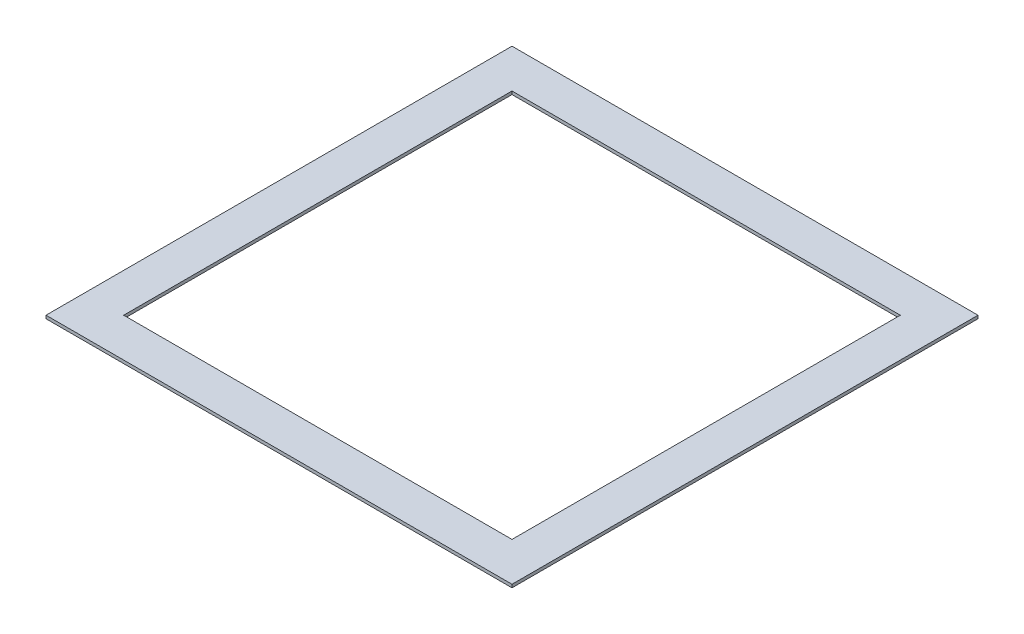
SolidWorks part; units mm, degrees
ref_plane "Front Plane" through (0, 0, 0) normal (0, 0, 1) x (1, 0, 0)
ref_plane "Top Plane" through (0, 0, 0) normal (0, 1, 0) x (1, 0, 0)
ref_plane "Right Plane" through (0, 0, 0) normal (1, 0, 0) x (0, 0, -1)
sketch "Sketch1" plane through (0, 0, 0) normal (0, 1, 0) x (1, 0, 0)
  line L1 (-600, -600) -> (600, -600)
  line L2 (-600, -600) -> (-600, 600)
  line L3 (-600, 600) -> (600, 600)
  line L4 (600, -600) -> (600, 600)
  line L5 (-600, -600) -> (600, 600) construction
  line L6 (-600, 600) -> (600, -600) construction
  line L7 (500, 500) -> (-500, 500)
  line L8 (500, 500) -> (500, -500)
  line L9 (500, -500) -> (-500, -500)
  line L10 (-500, 500) -> (-500, -500)
  line L11 (500, 500) -> (-500, -500) construction
  line L12 (500, -500) -> (-500, 500) construction
  point P0 (0, 0)
  point P6 (0, 0)
  dimension "D1" = 1200
  dimension "D2" = 1000
extrude "Extrude1" add sketch "Sketch1" against normal blind 8
